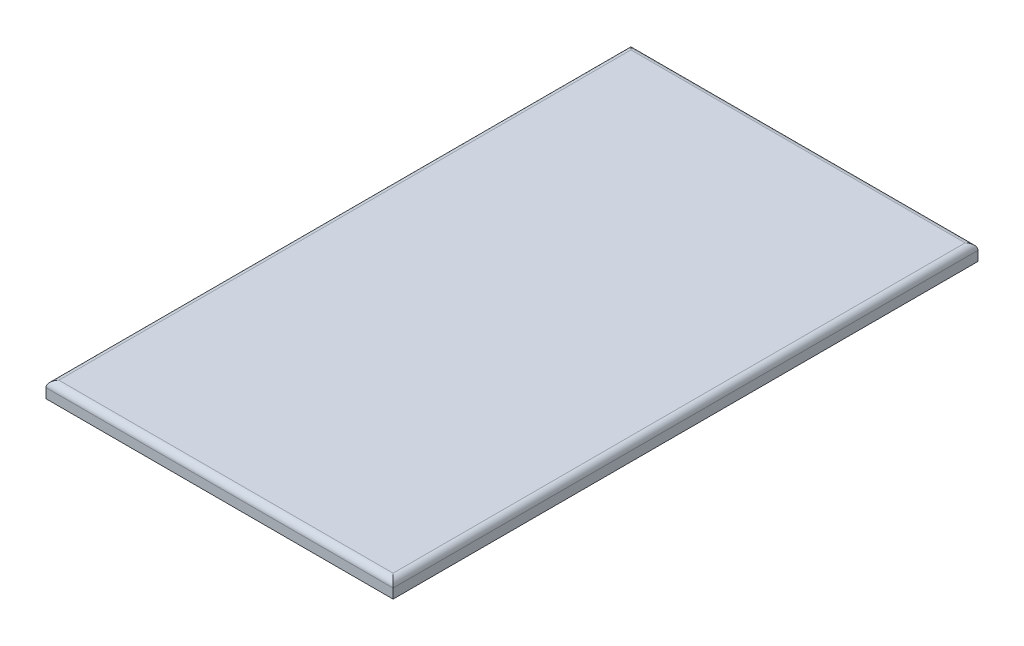
SolidWorks part; units mm, degrees
ref_plane "Front Plane" through (0, 0, 0) normal (0, 0, 1) x (1, 0, 0)
ref_plane "Top Plane" through (0, 0, 0) normal (0, 1, 0) x (1, 0, 0)
ref_plane "Right Plane" through (0, 0, 0) normal (1, 0, 0) x (0, 0, -1)
sketch "Sketch1" plane through (0, 0, 0) normal (0, 1, 0) x (1, 0, 0)
  line L1 (-27, 45.5) -> (27, 45.5)
  line L2 (-27, 45.5) -> (-27, -45.5)
  line L3 (-27, -45.5) -> (27, -45.5)
  line L4 (27, 45.5) -> (27, -45.5)
  line L5 (-27, 45.5) -> (27, -45.5) construction
  line L6 (-27, -45.5) -> (27, 45.5) construction
  point P0 (0, 0)
extrude "Boss-Extrude1" add sketch "Sketch1" along normal blind 2.5
fillet "Fillet1" radius 1 4 edges at (0, 2.5, 45.5) (-27, 2.5, 0) (0, 2.5, -45.5) (27, 2.5, 0)
